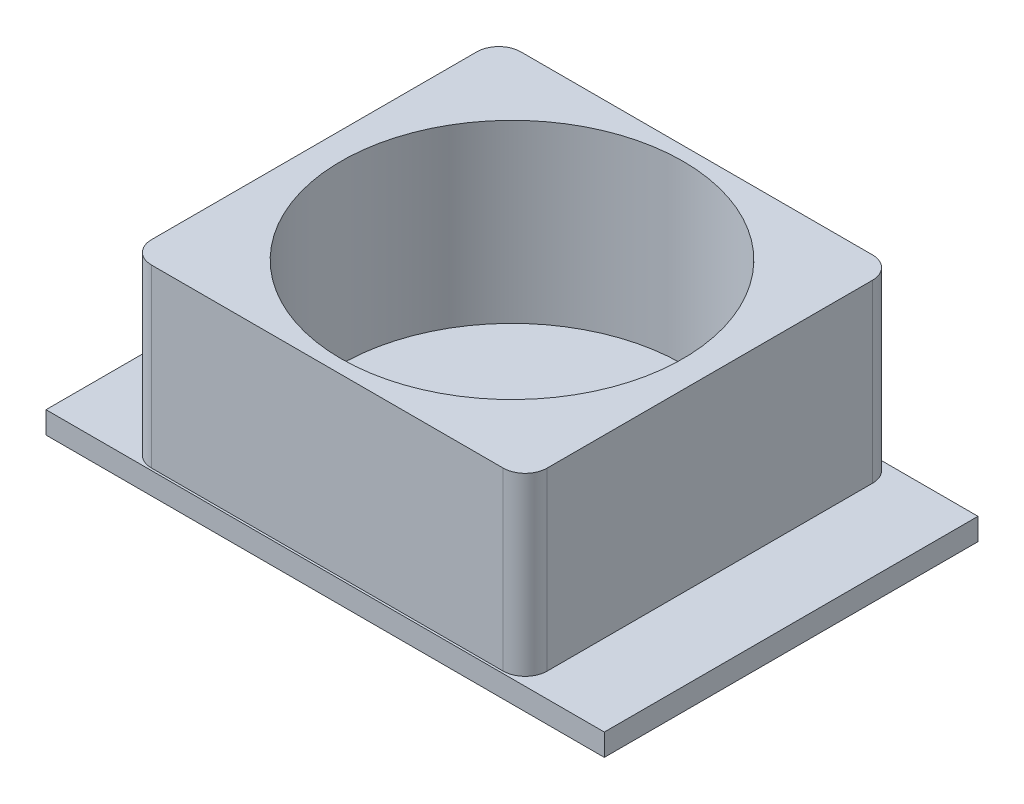
SolidWorks part; units mm, degrees
ref_plane "Front Plane" through (0, 0, 0) normal (0, 0, 1) x (1, 0, 0)
ref_plane "Top Plane" through (0, 0, 0) normal (0, 1, 0) x (1, 0, 0)
ref_plane "Right Plane" through (0, 0, 0) normal (1, 0, 0) x (0, 0, -1)
sketch "Sketch2" plane through (0, 0, 0) normal (0, 1, 0) x (1, 0, 0)
  line L0 (0, 42) -> (90, 42) construction
  line L1 (0, 0) -> (90, 0)
  line L2 (0, 0) -> (0, 84)
  line L3 (0, 84) -> (90, 84)
  line L4 (90, 0) -> (90, 84)
  line L5 (45, 84) -> (45, 0) construction
  line L6 (83.9, 42) -> (83.9, 0) construction
  line L7 (45, 3.1) -> (0, 3.1) construction
  circle A0 centre (45, 42) radius 38.9
  dimension "D3" = 77.8
  dimension "D5" = 3.1
  dimension "D1" = 90
  dimension "D2" = 84
  dimension "D4" = 6.1
extrude "Boss-Extrude1" add sketch "Sketch2" along normal blind 40
sketch "Sketch3" plane through (0, 0, 0) normal (0, -1, 0) x (1, 0, 0)
  line L0 (0, -42) -> (90, -42) construction
  line L1 (0, -84) -> (0, 0) construction
  line L2 (90, 0) -> (90, -84) construction
  line L4 (-18.5, 0.5) -> (108.5, 0.5)
  line L5 (-18.5, 0.5) -> (-18.5, -84.5)
  line L6 (-18.5, -84.5) -> (108.5, -84.5)
  line L7 (108.5, 0.5) -> (108.5, -84.5)
  line L8 (-18.5, 0.5) -> (108.5, -84.5) construction
  line L9 (-18.5, -84.5) -> (108.5, 0.5) construction
  point P6 (45, -42)
  dimension "D1" = 127
  dimension "D2" = 85
extrude "Boss-Extrude2" add sketch "Sketch3" along normal blind 5 contours L5 L4 L7 L6
fillet "Fillet1" radius 5 4 edges at (0, 20, -84) (90, 20, -84) (90, 20, 0) (0, 20, 0)
